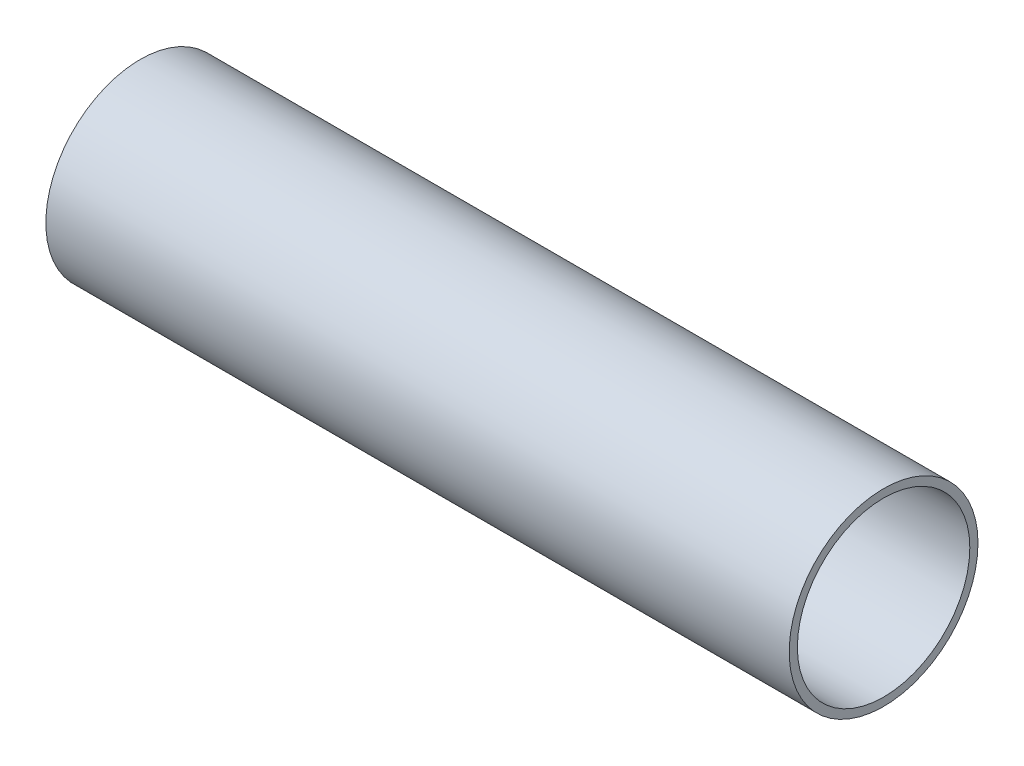
SolidWorks part; units mm, degrees
ref_plane "Alzado" through (0, 0, 0) normal (0, 0, 1) x (1, 0, 0)
ref_plane "Planta" through (0, 0, 0) normal (0, 1, 0) x (1, 0, 0)
ref_plane "Vista lateral" through (0, 0, 0) normal (1, 0, 0) x (0, 0, -1)
sketch "Croquis1" plane through (0, 0, 0) normal (1, 0, 0) x (0, 0, -1)
  circle A0 centre (0, 0) radius 19.05
  dimension "D1" = 38.1
extrude "Saliente-Extruir1" add sketch "Croquis1" along normal mid plane 150 contours A0
sketch "Croquis2" plane through (-75, 0, 0) normal (-1, 0, 0) x (0, 0, 1)
  circle A0 centre (0, 0) radius 17.4
  dimension "D1" = 34.8
extrude "Cortar-Extruir1" cut sketch "Croquis2" against normal blind 197 contours A0
